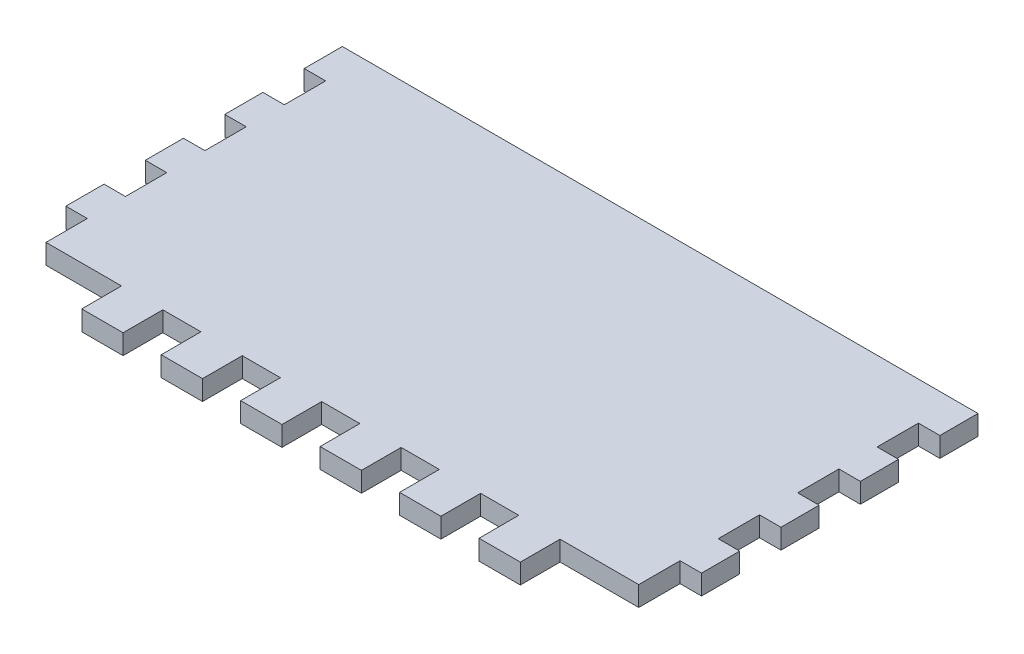
SolidWorks part; units mm, degrees
ref_plane "Front Plane" through (0, 0, 0) normal (0, 0, 1) x (1, 0, 0)
ref_plane "Top Plane" through (0, 0, 0) normal (0, 1, 0) x (1, 0, 0)
ref_plane "Right Plane" through (0, 0, 0) normal (1, 0, 0) x (0, 0, -1)
sketch "Sketch1" plane through (0, 0, 0) normal (0, 1, 0) x (1, 0, 0)
  line L1 (-50.8, -53.975) -> (50.8, -53.975)
  line L2 (-50.8, -53.975) -> (-50.8, 53.975)
  line L3 (-50.8, 53.975) -> (50.8, 53.975)
  line L4 (50.8, -53.975) -> (50.8, 53.975)
  line L5 (-50.8, -53.975) -> (50.8, 53.975) construction
  line L6 (-50.8, 53.975) -> (50.8, -53.975) construction
  line L11 (-41.275, -53.975) -> (41.275, 53.975) construction
  line L12 (-41.275, 53.975) -> (41.275, -53.975) construction
  point P0 (0, 0)
  point P5 (0, 0)
  dimension "D1" = 101.6
  dimension "D2" = 107.95
extrude "Boss-Extrude1" add sketch "Sketch1" along normal blind 3.175
sketch "Sketch2" plane through (0, 3.175, 0) normal (0, 1, 0) x (1, 0, 0)
  line L37 (22.098, -47.625) -> (28.194, -47.625)
  line L49 (28.194, -47.625) -> (28.194, -54.229)
  line L69 (0, 0) -> (0, -10.121) construction
  line L74 (-50.8, 53.975) -> (-50.8, -53.975) construction
  line L75 (-47.371, 28.448) -> (-50.8, 28.448)
  line L76 (-47.371, 28.448) -> (-47.371, 35.052)
  line L78 (-50.8, 28.448) -> (-50.8, 35.052)
  line L79 (-47.371, 22.479) -> (-50.8, 22.479)
  line L80 (-47.371, 22.479) -> (-47.371, 15.875)
  line L81 (-47.371, 15.875) -> (-50.8, 15.875)
  line L82 (-50.8, 22.479) -> (-50.8, 15.875)
  line L83 (-47.371, 9.779) -> (-50.8, 9.779)
  line L84 (-47.371, 9.779) -> (-47.371, 3.175)
  line L85 (-47.371, 3.175) -> (-50.8, 3.175)
  line L86 (-50.8, 9.779) -> (-50.8, 3.175)
  line L87 (-47.371, -2.921) -> (-50.8, -2.921)
  line L88 (-47.371, -2.921) -> (-47.371, -9.525)
  line L89 (-47.371, -9.525) -> (-50.8, -9.525)
  line L90 (-50.8, -2.921) -> (-50.8, -9.525)
  line L91 (-47.371, -15.621) -> (-50.8, -15.621)
  line L92 (-47.371, -15.621) -> (-47.371, -22.225)
  line L93 (-47.371, -22.225) -> (-50.8, -22.225)
  line L94 (-50.8, -15.621) -> (-50.8, -22.225)
  line L95 (-47.371, -28.321) -> (-50.8, -28.321)
  line L96 (-47.371, -28.321) -> (-47.371, -34.925)
  line L97 (-47.371, -34.925) -> (-50.8, -34.925)
  line L98 (-50.8, -28.321) -> (-50.8, -34.925)
  line L99 (-47.371, -41.021) -> (-50.8, -41.021)
  line L100 (-47.371, -41.021) -> (-47.371, -47.625)
  line L102 (-50.8, -41.021) -> (-50.8, -47.625)
  line L118 (50.8, -41.021) -> (50.8, -47.625)
  line L120 (47.371, -41.021) -> (47.371, -47.625)
  line L121 (47.371, -41.021) -> (50.8, -41.021)
  line L122 (50.8, -28.321) -> (50.8, -34.925)
  line L123 (47.371, -34.925) -> (50.8, -34.925)
  line L124 (47.371, -28.321) -> (47.371, -34.925)
  line L125 (47.371, -28.321) -> (50.8, -28.321)
  line L126 (50.8, -15.621) -> (50.8, -22.225)
  line L127 (47.371, -22.225) -> (50.8, -22.225)
  line L128 (47.371, -15.621) -> (47.371, -22.225)
  line L129 (47.371, -15.621) -> (50.8, -15.621)
  line L130 (50.8, -2.921) -> (50.8, -9.525)
  line L131 (47.371, -9.525) -> (50.8, -9.525)
  line L132 (47.371, -2.921) -> (47.371, -9.525)
  line L133 (47.371, -2.921) -> (50.8, -2.921)
  line L134 (50.8, 9.779) -> (50.8, 3.175)
  line L135 (47.371, 3.175) -> (50.8, 3.175)
  line L136 (47.371, 9.779) -> (47.371, 3.175)
  line L137 (47.371, 9.779) -> (50.8, 9.779)
  line L138 (50.8, 22.479) -> (50.8, 15.875)
  line L139 (47.371, 15.875) -> (50.8, 15.875)
  line L140 (47.371, 22.479) -> (47.371, 15.875)
  line L141 (47.371, 22.479) -> (50.8, 22.479)
  line L150 (-47.371, -53.721) -> (-50.8, -53.721) [skipped]
  line L151 (-47.371, -53.721) -> (-47.371, -60.325) [skipped]
  line L152 (-47.371, -60.325) -> (-50.8, -60.325) [skipped]
  line L153 (-50.8, -53.721) -> (-50.8, -60.325) [skipped]
  line L154 (-50.8, 35.052) -> (-47.371, 35.052)
  line L155 (50.8, 35.052) -> (47.371, 35.052)
  line L156 (50.8, 28.448) -> (50.8, 35.052)
  line L157 (47.371, 28.448) -> (47.371, 35.052)
  line L158 (47.371, 28.448) -> (50.8, 28.448)
  line L159 (-47.371, -47.625) -> (-35.306, -47.625)
  line L160 (-35.306, -47.625) -> (-35.306, -54.229)
  line L161 (-35.306, -54.229) -> (-28.702, -54.229)
  line L162 (-28.702, -54.229) -> (-28.702, -47.625)
  line L163 (-28.702, -47.625) -> (-22.606, -47.625)
  line L164 (-22.606, -47.625) -> (-22.606, -54.229)
  line L165 (-22.606, -54.229) -> (-16.002, -54.229)
  line L166 (-16.002, -54.229) -> (-16.002, -47.625)
  line L167 (-16.002, -47.625) -> (-9.906, -47.625)
  line L168 (-9.906, -47.625) -> (-9.906, -54.229)
  line L169 (-9.906, -54.229) -> (-3.302, -54.229)
  line L170 (-3.302, -54.229) -> (-3.302, -47.625)
  line L171 (-3.302, -47.625) -> (2.794, -47.625)
  line L172 (2.794, -47.625) -> (2.794, -54.229)
  line L173 (2.794, -54.229) -> (9.398, -54.229)
  line L174 (9.398, -54.229) -> (9.398, -47.625)
  line L175 (9.398, -47.625) -> (15.494, -47.625)
  line L176 (15.494, -47.625) -> (15.494, -54.229)
  line L177 (15.494, -54.229) -> (22.098, -54.229)
  line L178 (22.098, -54.229) -> (22.098, -47.625)
  line L180 (-50.8, -47.625) -> (-50.8, -92.545)
  line L181 (-47.371, -47.625) -> (-50.8, -47.625) [skipped]
  line L182 (-50.8, -92.545) -> (50.8, -92.545)
  line L183 (50.8, -92.545) -> (50.8, -47.625)
  line L184 (28.194, -54.229) -> (34.798, -54.229)
  line L185 (34.798, -54.229) -> (34.798, -47.625)
  line L186 (34.798, -47.625) -> (47.371, -47.625)
  line L187 (50.8, 53.975) -> (-50.8, 53.975) construction
  line L188 (50.8, 47.752) -> (47.371, 47.752)
  line L189 (50.8, 41.148) -> (50.8, 47.752)
  line L190 (47.371, 41.148) -> (47.371, 47.752)
  line L191 (47.371, 41.148) -> (50.8, 41.148)
  line L192 (-47.371, 41.148) -> (-50.8, 41.148)
  line L193 (-47.371, 41.148) -> (-47.371, 47.752)
  line L194 (-50.8, 41.148) -> (-50.8, 47.752)
  line L195 (-50.8, 47.752) -> (-47.371, 47.752)
  point P0 (-28.702, -50.927)
  dimension "D2" = 15.494
  dimension "D3" = 6.604
  dimension "D5" = 6.096
  dimension "D6" = 101.6
  dimension "D7" = 6.604
  dimension "D8" = 3.429
  dimension "D9" = 2
  dimension "D10" = 6.604
  dimension "D12" = 2
  dimension "D4" = 6.096
  dimension "D14" = 5.969
  dimension "D11" = 7
extrude "Cut-Extrude1" cut sketch "Sketch2" against normal through all both and the other way through all
sketch "Sketch3" plane through (0, 3.175, 0) normal (0, 1, 0) x (1, 0, 0)
  line L0 (-47.371, -47.625) -> (-35.306, -47.625) construction
  line L1 (-50.8, 53.975) -> (50.8, 53.975)
  line L2 (-50.8, 53.975) -> (-50.8, 3.175)
  line L3 (-50.8, 3.175) -> (50.8, 3.175)
  line L4 (50.8, 53.975) -> (50.8, 3.175)
  line L5 (50.8, 35.052) -> (50.8, 41.148) construction
  dimension "D1" = 50.8
extrude "Cut-Extrude2" cut sketch "Sketch3" against normal through all
